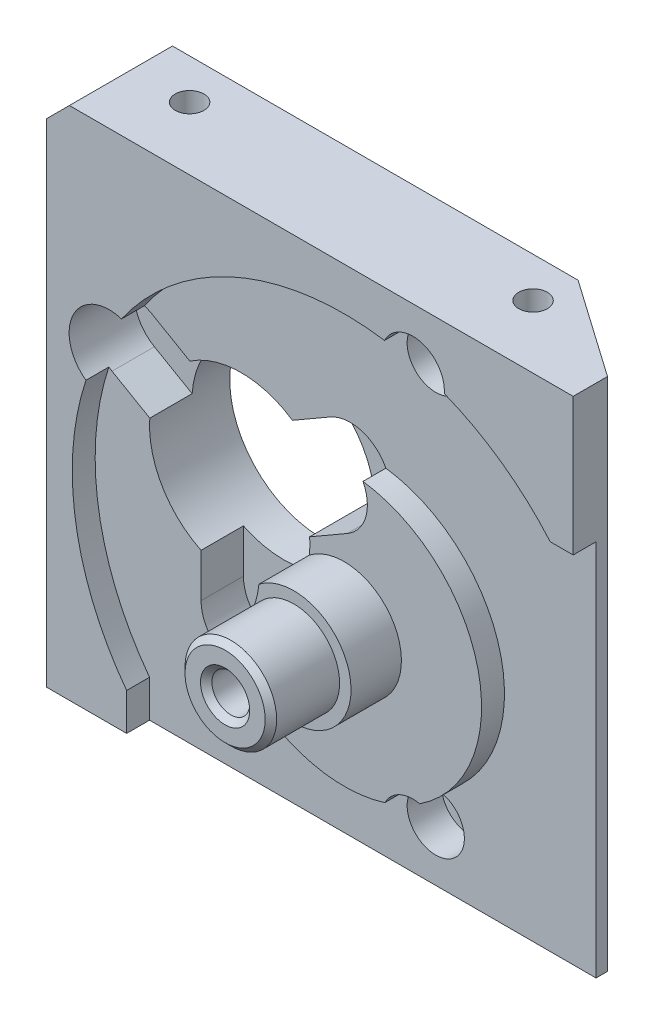
SolidWorks part; units mm, degrees
material "6061-T6 (SS)"
ref_plane "前视基准面" through (0, 0, 0) normal (0, 0, 1) x (1, 0, 0)
ref_plane "上视基准面" through (0, 0, 0) normal (0, 1, 0) x (1, 0, 0)
ref_plane "右视基准面" through (0, 0, 0) normal (1, 0, 0) x (0, 0, -1)
sketch "草图1" plane through (0, 0, 0) normal (0, 0, 1) x (1, 0, 0)
  line L0 (0, 23.5) -> (0, -23.5) construction
  line L1 (-26, 23.5) -> (26, 23.5)
  line L2 (-26, 23.5) -> (-26, -23.5)
  line L3 (-26, -23.5) -> (26, -23.5)
  line L4 (26, 23.5) -> (26, -23.5)
  dimension "D1" = 52
  dimension "D2" = 47
extrude "拉伸1" add sketch "草图1" along normal blind 9
sketch "草图19" plane through (0, 0, 9) normal (0, 0, 1) x (1, 0, 0)
  line L0 (26, -23.5) -> (26, 23.5) construction
  line L1 (-26, -23.5) -> (26, -23.5) construction
  circle A0 centre (0, -4) radius 12
  circle A1 centre (0, -4) radius 23.75
  dimension "D3" = 24
  dimension "D4" = 47.5
  dimension "D1" = 26
  dimension "D2" = 19.5
extrude "拉伸2" cut sketch "草图19" against normal blind 2
sketch "草图20" plane through (0, 0, 9) normal (0, 0, 1) x (1, 0, 0)
  circle A0 centre (0, -4) radius 5
  dimension "D1" = 10
extrude "拉伸3" add sketch "草图20" along normal blind 4.4
sketch "草图21" plane through (0, 0, 13.4) normal (0, 0, 1) x (1, 0, 0)
  circle A0 centre (0, -4) radius 4
  dimension "D1" = 8
extrude "拉伸4" add sketch "草图21" along normal blind 6
sketch "草图22" plane through (0, 0, 9) normal (0, 0, 1) x (1, 0, 0)
  line L0 (-26, 23.5) -> (-26, -23.5) construction
  circle A0 centre (-11, 0.7958) radius 8
  circle A2 centre (0, -4) radius 4 construction
  dimension "D3" = 16
  dimension "D1" = 15
  dimension "D2" = 12
extrude "拉伸5" cut sketch "草图22" against normal through all
sketch "草图23" plane through (0, 0, 7) normal (0, 0, 1) x (1, 0, 0)
  line L0 (-11, 0.7958) -> (-11, -10.2042)
  line L1 (-11, 0.7958) -> (-1.4737, 6.2958)
  line L2 (-11, 0.7958) -> (-20.5263, 6.2958)
  circle A0 centre (-11, 0.7958) radius 11
  dimension "D1" = 22
  dimension "D2" = 120
  dimension "D3" = 120
sketch "草图25" plane through (0, -23.5, 0) normal (0, -1, 0) x (1, 0, 0)
  line L0 (26, 8) -> (14.5748, 0)
  line L1 (26, 9) -> (26, 0) construction
  line L2 (-26, 0) -> (26, 0) construction
  line L3 (14.5748, 0) -> (26, 0)
  line L4 (26, 0) -> (26, 8)
  dimension "D1" = 8
  dimension "D2" = 35
extrude "拉伸6" cut sketch "草图25" against normal up to surface (47 mm away) up to face at (0, 23.5, 4.5)
sketch "草图27" plane through (0, 23.5, 0) normal (0, 1, 0) x (1, 0, 0)
  line L0 (11, -3.5) -> (-19, -3.5)
  line L1 (14.5748, 0) -> (-26, 0) construction
  line L2 (26, -9) -> (26, -8) construction
  dimension "D1" = 3.5
  dimension "D2" = 15
  dimension "D3" = 30
hole_wizard "M3 螺纹孔1" positions "3D草图3" profile "草图28" tap size "M3" standard "GB"
sketch3d "3D草图3"
  point P3 (11, 23.5, 3.5)
  point P6 (-19, 23.5, 3.5)
sketch "草图28" plane through (11, 23.5, 3.5) normal (1, 0, 0) x (0, 0, 1)
  line L0 (0, 0) -> (0, 10.2511)
  line L1 (0, 10.2511) -> (1.25, 9.5)
  line L2 (1.25, 9.5) -> (1.25, 0)
  line L5 (1.25, 0) -> (0, 0)
  line L10 (0, 10.2511) -> (-1.25, 9.5) construction
  line L11 (0, -6.35) -> (0, 107.95) construction
  dimension "螺纹孔钻头直径" = 2.5
  dimension "螺纹孔钻头深度" = 9.5
  dimension "导头角度" = 118
cosmetic thread "孔螺蚊线5" parameters "D1"=8, "D2"=3
cosmetic thread "孔螺蚊线8" parameters "D1"=8, "D2"=3
hole_wizard "M4 螺纹孔2" positions "3D草图4" profile "草图29" tap size "M4" standard "GB"
sketch3d "3D草图4"
  line L0 (0, -4, 19.4) -> (0, -4, 13.4) construction
  point P0 (0, -4, 19.4)
sketch "草图29" plane through (0, -4, 19.4) normal (1, 0, 0) x (0, -1, 0)
  line L0 (0, 0) -> (0, 11.0914)
  line L1 (0, 11.0914) -> (1.65, 10.1)
  line L2 (1.65, 10.1) -> (1.65, 0)
  line L5 (1.65, 0) -> (0, 0)
  line L10 (0, 11.0914) -> (-1.65, 10.1) construction
  line L11 (0, -6.35) -> (0, 107.95) construction
  dimension "螺纹孔钻头直径" = 3.3
  dimension "螺纹孔钻头深度" = 10.1
  dimension "导头角度" = 118
cosmetic thread "孔螺蚊线4" parameters "D1"=8, "D2"=4
chamfer "倒角3" distance 0.5 angle 45 2 edges at (1.65, -4, 19.4) (4, -4, 19.4)
sketch "草图30" plane through (0, -23.5, 0) normal (0, -1, 0) x (1, 0, 0)
  line L0 (11, 3) -> (-24, 3)
  line L1 (26, 9) -> (26, 8) construction
  line L2 (-26, 0) -> (14.5748, 0) construction
  dimension "D1" = 35
  dimension "D2" = 15
  dimension "D3" = 3
chamfer "倒角5" distance 2 angle 45 1 edges at (-26, 23.5, 4.5)
sketch "草图32" plane through (0, 0, 9) normal (0, 0, 1) x (1, 0, 0)
  line L0 (6.7, 23.5) -> (6.7, 17)
  line L1 (26, 23.5) -> (-24, 23.5) construction
  line L2 (-26, 21.5) -> (-26, -23.5) construction
  line L3 (6.7, -23.5) -> (6.7, -18)
  line L4 (-13.5577, -23.5) -> (13.5577, -23.5) construction
  dimension "D1" = 32.7
  dimension "D2" = 6.5
  dimension "D3" = 5.5
sketch "Sketch3" plane through (0, -23.5, 0) normal (0, -1, 0) x (1, 0, 0)
  line L0 (0, 19.4) -> (0, -50.6)
  line L1 (2.15, 19.4) -> (-2.15, 19.4) construction
  line L2 (0, 19.4) -> (0, 39.4)
  dimension "D1" = 20
  dimension "D2" = 70
sketch "Sketch4" plane through (0, -23.5, 0) normal (0, -1, 0) x (1, 0, 0)
  line L9 (-26, 0) -> (14.5748, 0)
  line L10 (14.5748, 0) -> (26, 8)
  line L11 (26, 8) -> (26, 9)
  line L12 (26, 9) -> (13.5577, 9)
  line L13 (13.5577, 9) -> (13.5577, 7)
  line L14 (13.5577, 7) -> (-13.5577, 7)
  line L15 (-13.5577, 7) -> (-13.5577, 9)
  line L16 (-13.5577, 9) -> (-26, 9)
  line L17 (-26, 9) -> (-26, 0)
  line L18 (-26, 0) -> (14.5748, 0)
  line L19 (14.5748, 0) -> (26, 8)
  line L20 (26, 8) -> (26, 9)
  line L21 (26, 9) -> (13.5577, 9)
  line L22 (13.5577, 9) -> (13.5577, 7)
  line L23 (13.5577, 7) -> (-13.5577, 7)
  line L24 (-13.5577, 7) -> (-13.5577, 9)
  line L25 (-13.5577, 9) -> (-26, 9)
  line L26 (-26, 9) -> (-26, 0)
  dimension "D1" = 0
extrude "Extrude3" cut sketch "Sketch4" against normal blind 2
sketch "Sketch5" plane through (0, -21.5, 0) normal (0, -1, 0) x (1, 0, 0)
  line L0 (26, 9) -> (20, 9)
  line L1 (26, 9) -> (16.0565, 9) construction
  line L2 (20, 9) -> (20, 6)
  line L3 (20, 6) -> (11.4311, 0)
  line L4 (-26, 0) -> (14.5748, 0) construction
  line L5 (11.4311, 0) -> (14.5748, 0)
  line L6 (14.5748, 0) -> (26, 8)
  line L7 (26, 8) -> (26, 9)
  dimension "D1" = 6
  dimension "D2" = 3
extrude "Extrude4" cut sketch "Sketch5" against normal up to surface (45 mm away) up to face at (11, 23.5, 4.75)
sketch "草图34" plane through (0, 0, 0) normal (0, 0, -1) x (-1, 0, 0)
  circle A0 centre (11, 0.7958) radius 8
extrude "切除-拉伸1" cut sketch "草图34" against normal blind 31
sketch "草图35" plane through (0, 0, 7) normal (0, 0, 1) x (1, 0, 0)
  circle A0 centre (-1.4737, 6.2958) radius 3.25
  dimension "D1" = 6.5
extrude "切除-拉伸2" cut sketch "草图35" along normal blind 33
pattern_circular "阵列(圆周)1" count 3 over 360 about axis through (-11, 0.7958, 0) along (0, 0, 1) of "切除-拉伸2"
hole_wizard "打孔尺寸(%根据)内六角圆柱头螺钉的类型2" positions "3D草图7" profile "草图36" counterbore size "M3" standard "GB"
sketch3d "3D草图7"
  point P0 (-20.5263, 6.2958, 7)
  point P3 (-1.4737, 6.2958, 7)
  point P6 (-11, -10.2042, 7)
sketch "草图36" plane through (-20.5263, 6.2958, 7) normal (1, 0, 0) x (0, -1, 0)
  line L0 (0, 0) -> (0, 7)
  line L1 (0, 7) -> (1.5, 7)
  line L3 (1.5, 7) -> (1.5, 3.7)
  line L4 (1.5, 3.7) -> (3.5, 3.7)
  line L5 (3.5, 3.7) -> (3.5, 0)
  line L7 (3.5, 0) -> (0, 0)
  line L11 (0, -6.35) -> (0, 107.95) construction
  dimension "通孔孔直径" = 3
  dimension "通孔孔深度" = 7
  dimension "柱形沉头孔直径" = 7
  dimension "柱形沉头孔深度" = 3.7
sketch "草图37" plane through (0, -21.5, 0) normal (0, -1, 0) x (1, 0, 0)
  line L0 (-16.0565, 7) -> (-26, 7) construction
  line L1 (-26, 9) -> (-26, 0) construction
  line L2 (-26, 7) -> (-26, 0) construction
  line L3 (-26, 3.5) -> (-24, 3.5) construction
  line L4 (-24, 3.5) -> (11, 3.5) construction
  dimension "D1" = 2
  dimension "D2" = 35
hole_wizard "M3 螺纹孔2" positions "3D草图8" profile "草图38" tap size "M3" standard "GB"
sketch3d "3D草图8"
  point P0 (-24, -21.5, 3.5)
  point P3 (11, -21.5, 3.5)
sketch "草图38" plane through (-24, -21.5, 3.5) normal (1, 0, 0) x (0, 0, -1)
  line L0 (0, 0) -> (0, 10.2511)
  line L1 (0, 10.2511) -> (1.25, 9.5)
  line L2 (1.25, 9.5) -> (1.25, 0)
  line L5 (1.25, 0) -> (0, 0)
  line L10 (0, 10.2511) -> (-1.25, 9.5) construction
  line L11 (0, -6.35) -> (0, 107.95) construction
  dimension "螺纹孔钻头直径" = 2.5
  dimension "螺纹孔钻头深度" = 9.5
  dimension "导头角度" = 118
cosmetic thread "孔螺蚊线6" parameters "D1"=8, "D2"=3
cosmetic thread "孔螺蚊线7" parameters "D1"=8, "D2"=3
sketch "草图39" plane through (0, 0, 0) normal (0, 0, -1) x (-1, 0, 0)
  circle A0 centre (-6, 18.2958) radius 2
  circle A1 centre (-6, -16.7042) radius 2
extrude "切除-拉伸3" cut sketch "草图39" against normal blind 2
sketch "草图40" plane through (0, 0, 9) normal (0, 0, 1) x (1, 0, 0)
  circle A0 centre (6, 18.2958) radius 2.75
  circle A1 centre (6, -16.7042) radius 2.75
  dimension "D1" = 5.5
extrude "切除-拉伸4" cut sketch "草图40" against normal up to surface (2 mm away) up to face at (-4.7752, -1.8022, 7)
sketch "草图41" plane through (0, 0, 2) normal (0, 0, -1) x (-1, 0, 0)
  circle A0 centre (-6, 18.2958) radius 1.1
  circle A1 centre (-6, -16.7042) radius 1.1
  dimension "D1" = 2.2
extrude "切除-拉伸5" cut sketch "草图41" against normal blind 37
chamfer "倒角7" distance 0.5 angle 45 2 edges at (4, -16.7042, 0) (4, 18.2958, 0)
hole_wizard "打孔尺寸(%根据)内六角圆柱头螺钉的类型2" positions "3D草图9" profile "草图42" counterbore size "M2" standard "GB" end condition through all
sketch3d "3D草图9"
  line L3 (6, 18.2958, 7) -> (6, 18.2958, 2) construction
  line L4 (6, -16.7042, 7) -> (6, -16.7042, 2) construction
  point P15 (6, 18.2958, 7)
  point P22 (6, -16.7042, 7)
sketch "草图42" plane through (6, 18.2958, 7) normal (1, 0, 0) x (0, -1, 0)
  line L0 (0, 0) -> (0, 7)
  line L1 (0, 7) -> (1, 7)
  line L3 (1, 7) -> (1, 3)
  line L4 (1, 3) -> (2.5, 3)
  line L5 (2.5, 3) -> (2.5, 0)
  line L7 (2.5, 0) -> (0, 0)
  line L11 (0, -6.35) -> (0, 107.95) construction
  dimension "通孔孔直径" = 2
  dimension "通孔孔深度" = 7
  dimension "柱形沉头孔直径" = 5
  dimension "柱形沉头孔深度" = 3
sketch "草图44" plane through (0, 0, 3.3) normal (0, 0, 1) x (1, 0, 0)
  line L3 (-1.4737, 6.2958) -> (-11, 0.7958) construction
  line L4 (0.2763, 3.2647) -> (-9.25, -2.2353)
  line L5 (-3.2237, 9.3269) -> (-12.75, 3.8269)
  arc A2 (0.2763, 3.2647) -> (-3.2237, 9.3269) centre (-1.4737, 6.2958) ccw
  arc A3 (-12.75, 3.8269) -> (-9.25, -2.2353) centre (-11, 0.7958) ccw
  point P11 (-6.2369, 3.5458)
  dimension "D1" = 3.5
extrude "切除-拉伸7" cut sketch "草图44" along normal blind 7
pattern_circular "阵列(圆周)2" count 3 over 360 about axis through (-11, 0.7958, 0) along (0, 0, 1) of "切除-拉伸7"
sketch "草图45" plane through (0, 0, 9) normal (0, 0, 1) x (1, 0, 0)
  line L1 (-16.0565, -21.5) -> (-19, -21.5)
  line L2 (-16.0565, -21.5) -> (-16.0565, -18.25)
  line L3 (-16.0565, -18.25) -> (-19, -18.25)
  line L4 (-19, -21.5) -> (-19, -18.25)
  line L5 (20, 8.8087) -> (17.9948, 8.8087)
  line L6 (20, 8.8087) -> (20, 11.5)
  line L7 (20, 11.5) -> (17.9948, 11.5)
  line L8 (17.9948, 8.8087) -> (17.9948, 11.5)
  line L9 (20, -21.5) -> (16.0565, -21.5)
  line L10 (20, -21.5) -> (20, -16.7362)
  line L11 (20, -16.7362) -> (16.0565, -16.7362)
  line L12 (16.0565, -21.5) -> (16.0565, -16.7362)
  line L13 (-26, 21.5) -> (-26, -21.5) construction
  line L15 (20, 23.5) -> (-24, 23.5) construction
  arc A0 (-22.5537, 3.4428) -> (-16.0565, -21.5) centre (0, -4) ccw construction
  arc A1 (20, 8.8087) -> (8.7417, 18.0827) centre (0, -4) ccw construction
  dimension "D1" = 7
  dimension "D2" = 12
extrude "切除-拉伸8" cut sketch "草图45" against normal blind 2
